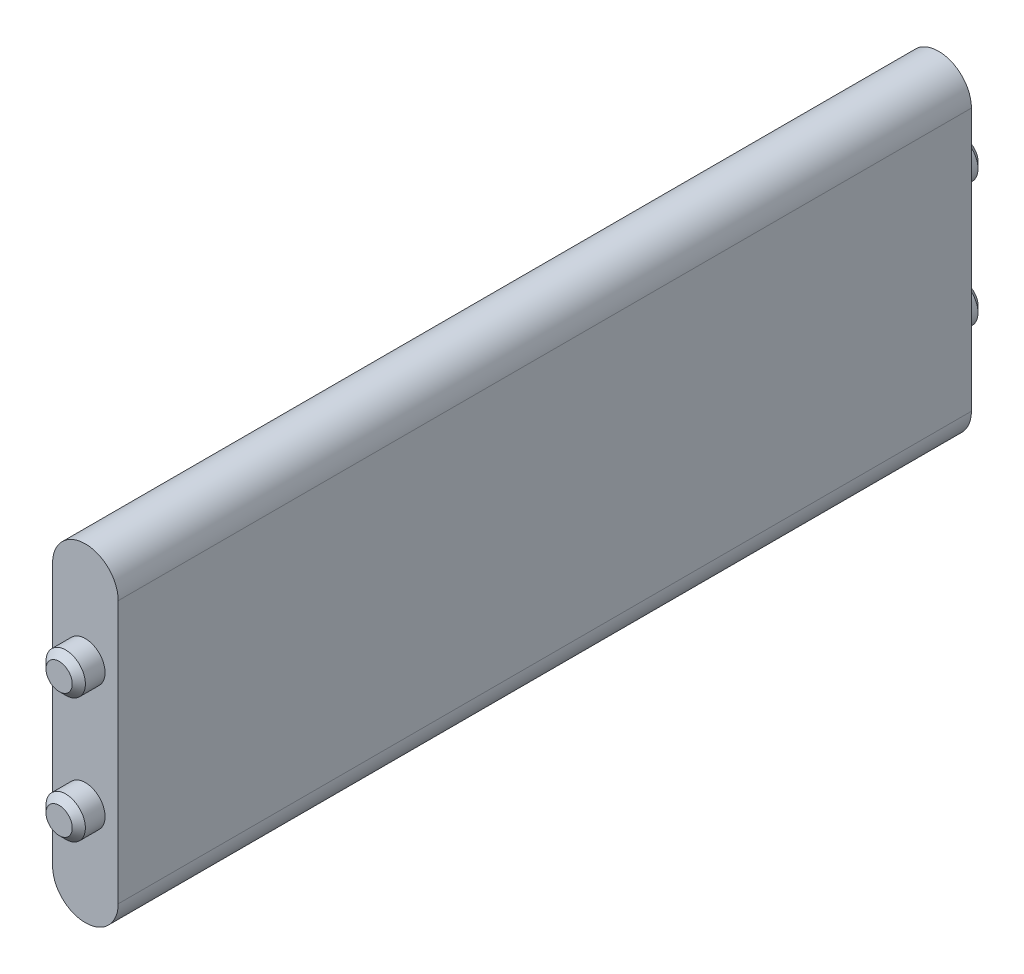
SolidWorks part; units mm, degrees
ref_plane "前基準面" through (0, 0, 0) normal (0, 0, 1) x (1, 0, 0)
ref_plane "上基準面" through (0, 0, 0) normal (0, 1, 0) x (1, 0, 0)
ref_plane "右基準面" through (0, 0, 0) normal (1, 0, 0) x (0, 0, -1)
sketch "草圖1" plane through (0, 0, 0) normal (0, 0, 1) x (1, 0, 0)
  line L0 (0, 20) -> (0, -20) construction
  line L1 (-5, 20) -> (-5, -20)
  line L2 (5, 20) -> (5, -20)
  arc A0 (-5, 20) -> (5, 20) centre (0, 20) cw
  arc A1 (-5, -20) -> (5, -20) centre (0, -20) ccw
  dimension "D2" = 50
  dimension "D1" = 10
extrude "伸長1" add sketch "草圖1" along normal mid plane 130
sketch "草圖2" plane through (0, 0, 65) normal (0, 0, 1) x (1, 0, 0)
  line L0 (0, 0) -> (9.6203, 0) construction
  line L1 (0, 0) -> (0, 9.5) construction
  circle A0 centre (0, 9.5) radius 3
  circle A1 centre (0, -9.5) radius 3
  dimension "D1" = 6
  dimension "D2" = 19
extrude "伸長2" add sketch "草圖2" along normal blind 4
chamfer "導角1" distance 1 angle 45 2 edges at (-3, -9.5, 69) (3, 9.5, 69)
mirror "鏡射1" about plane through (0, 0, 0) normal (0, 0, 1) of "伸長2", "導角1"
